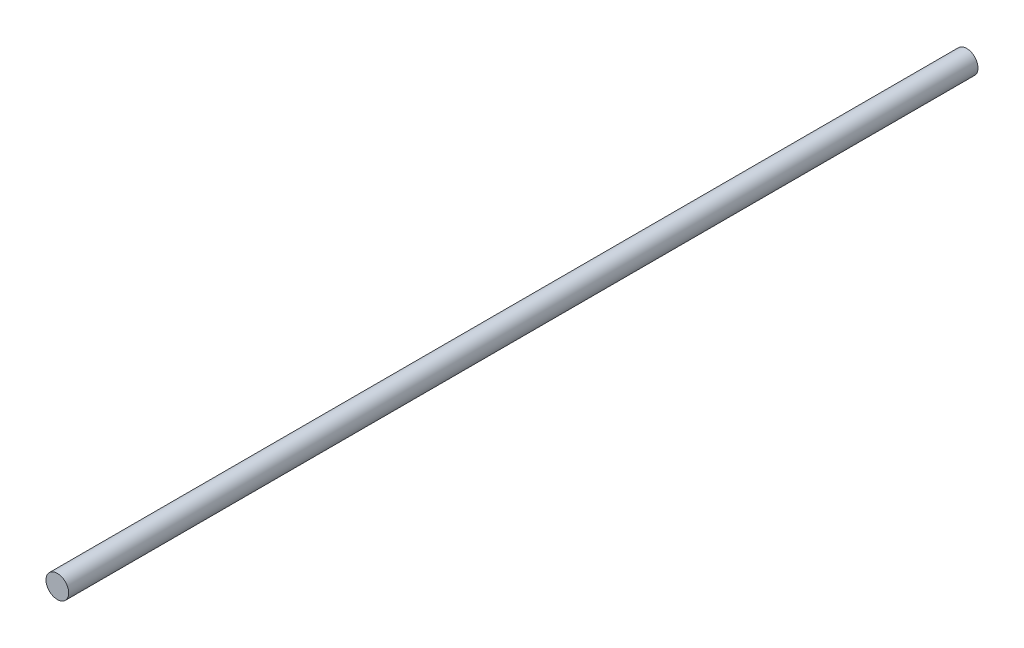
SolidWorks part; units mm, degrees
ref_plane "Plan de face" through (0, 0, 0) normal (0, 0, 1) x (1, 0, 0)
ref_plane "Plan de dessus" through (0, 0, 0) normal (0, 1, 0) x (1, 0, 0)
ref_plane "Plan de droite" through (0, 0, 0) normal (1, 0, 0) x (0, 0, -1)
sketch "Esquisse1" plane through (0, 0, 0) normal (0, 0, 1) x (1, 0, 0)
  circle A0 centre (0, 0) radius 3
extrude "Boss.-Extru.1" add sketch "Esquisse1" along normal blind 240
